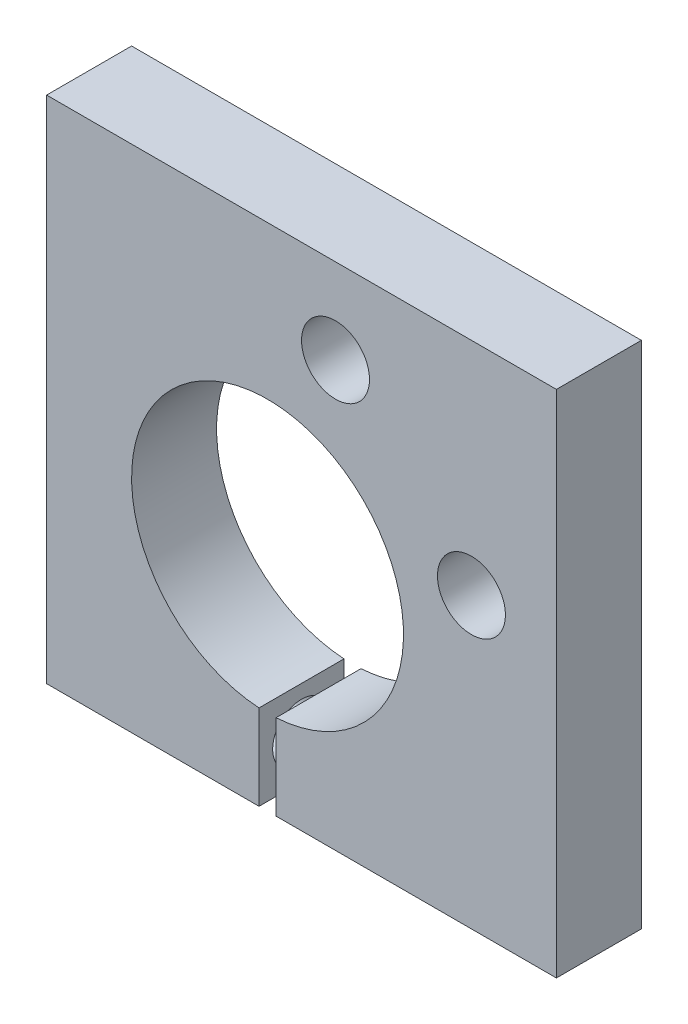
SolidWorks part; units mm, degrees
material "Lega 1060"
ref_plane "Piano frontale" through (0, 0, 0) normal (0, 0, 1) x (1, 0, 0)
ref_plane "Piano superiore" through (0, 0, 0) normal (0, 1, 0) x (1, 0, 0)
ref_plane "Piano destro" through (0, 0, 0) normal (1, 0, 0) x (0, 0, -1)
sketch "Schizzo1" plane through (0, 0, 0) normal (0, 0, 1) x (1, 0, 0)
  line L0 (0, 0) -> (30, 30) construction
  line L1 (0, 0) -> (30, 0)
  line L2 (0, 0) -> (0, 30)
  line L3 (0, 30) -> (30, 30)
  line L4 (30, 0) -> (30, 30)
  line L5 (12.5, 0) -> (12.5, 5.0156)
  line L6 (13.5, 0) -> (13.5, 5.0156)
  line L7 (13, 13) -> (13, 9.9239) construction
  arc A0 (13.5, 5.0156) -> (12.5, 5.0156) centre (13, 13) ccw
  circle A1 centre (17, 25) radius 2
  circle A2 centre (25, 17) radius 2
  circle A3 centre (13, 13) radius 8 construction
  dimension "D1" = 16
  dimension "D6" = 4
  dimension "D4" = 5
  dimension "D2" = 30
  dimension "D5" = 1
  dimension "D7" = 5
  dimension "D8" = 13
extrude "Estrusione-Estrusione1" add sketch "Schizzo1" along normal blind 5 contours A0 L6 L1 L4 L3 L2 L5 A2 A1
hole_wizard "Foro per Vite M3-1" positions "Schizzo3" profile "Schizzo2" hole size "M3" standard "ISO"
sketch "Schizzo3" plane through (0, 0, 0) normal (-1, 0, 0) x (0, 0, 1)
  line L0 (0, 5.0156) -> (5, 0) construction
  line L2 (5, 5.0156) -> (0, 0) construction
  point P0 (2.5, 2.5078)
sketch "Schizzo2" plane through (0, 2.5078, 2.5) normal (0, 1, 0) x (0, 0, 1)
  line L0 (0, 0) -> (0, 12.5)
  line L1 (0, 12.5) -> (1.7, 12.5)
  line L2 (1.7, 12.5) -> (1.7, 0)
  line L5 (1.7, 0) -> (0, 0)
  line L11 (0, -6.35) -> (0, 107.95) construction
  dimension "Thru Hole Dia." = 3.4
  dimension "Thru Hole Depth" = 12.5
hole_wizard "Foro filettato M3-1" positions "Schizzo5" profile "Schizzo4" tap size "M3" standard "ISO"
sketch "Schizzo5" plane through (13.5, 0, 0) normal (-1, 0, 0) x (0, 0, 1)
  circle A0 centre (2.5, 2.5078) radius 1.7 construction
  point P1 (2.5, 2.5078)
sketch "Schizzo4" plane through (13.5, 2.5078, 2.5) normal (0, 1, 0) x (0, 0, 1)
  line L0 (0, 0) -> (0, 5.2511)
  line L1 (0, 5.2511) -> (1.25, 4.5)
  line L2 (1.25, 4.5) -> (1.25, 0)
  line L5 (1.25, 0) -> (0, 0)
  line L10 (0, 5.2511) -> (-1.25, 4.5) construction
  line L11 (0, -6.35) -> (0, 107.95) construction
  dimension "Tap Drill Dia." = 2.5
  dimension "Tap Drill Depth" = 4.5
  dimension "Drill Angle" = 118
cosmetic thread "Filettatura del foro1" parameters "D1"=2, "D2"=3
